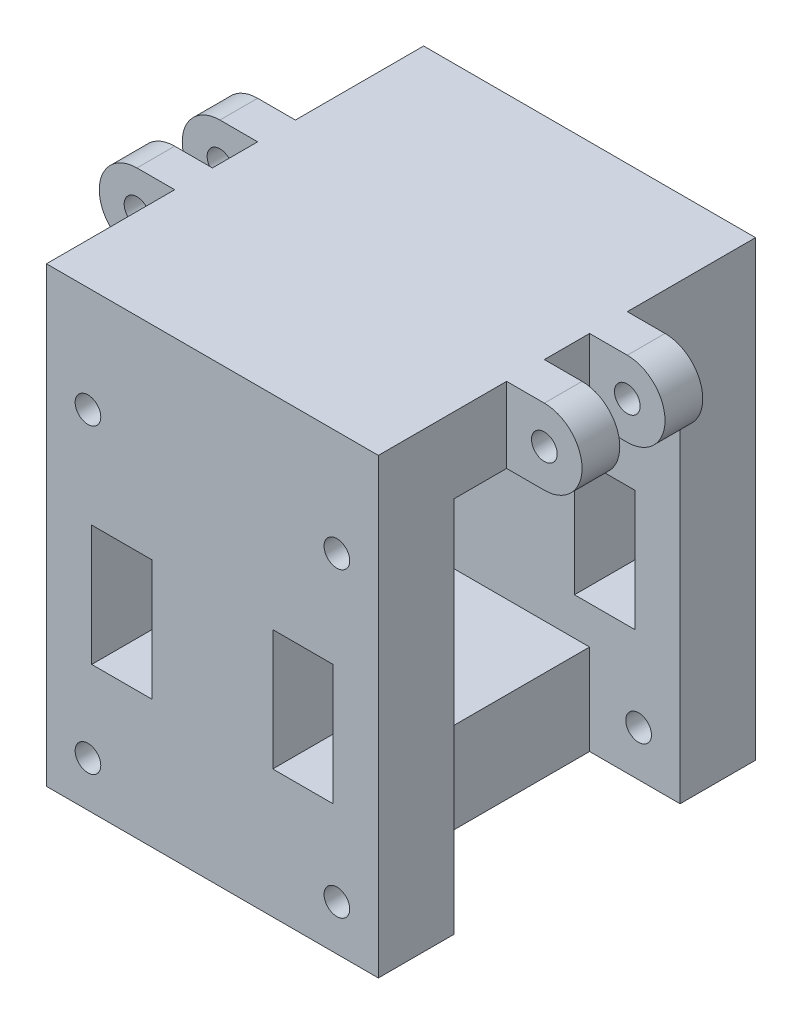
SolidWorks part; units mm, degrees
ref_plane "Front Plane" through (0, 0, 0) normal (0, 0, 1) x (1, 0, 0)
ref_plane "Top Plane" through (0, 0, 0) normal (0, 1, 0) x (1, 0, 0)
ref_plane "Right Plane" through (0, 0, 0) normal (1, 0, 0) x (0, 0, -1)
sketch "Sketch1" plane through (0, 0, 0) normal (0, 0, 1) x (1, 0, 0)
  line L1 (-25, 30) -> (25, 30)
  line L2 (-25, 30) -> (-25, -30)
  line L3 (-25, -30) -> (25, -30)
  line L4 (25, 30) -> (25, -30)
  line L5 (-25, 30) -> (25, -30) construction
  line L6 (-25, -30) -> (25, 30) construction
  point P0 (0, 0)
  dimension "D1" = 50
  dimension "D2" = 60
extrude "Boss-Extrude1" add sketch "Sketch1" along normal blind 50
sketch "Sketch2" plane through (25, 0, 0) normal (1, 0, 0) x (0, 0, -1)
  line L0 (-50, -30) -> (0, -30) construction
  line L1 (-40, -30) -> (-10, -30)
  line L2 (-40, -30) -> (-40, 20)
  line L3 (-40, 20) -> (-10, 20)
  line L4 (-10, -30) -> (-10, 20)
  line L5 (-25, 30) -> (-25, -49970) construction
  line L6 (-50, 30) -> (0, 30) construction
  point P10 (-25, 30)
  point P11 (-25, -30)
  dimension "D1" = 30
  dimension "D2" = 10
extrude "Cut-Extrude1" cut sketch "Sketch2" against normal through all
sketch "Sketch3" plane through (0, 0, 50) normal (0, 0, 1) x (1, 0, 0)
  line L0 (-25, -30) -> (25, -30) construction
  line L1 (-25, 30) -> (-25, -30) construction
  line L2 (0, 0) -> (0, -50000) construction
  circle A0 centre (-16.5, -24) radius 1.7
  circle A1 centre (-16.5, 16) radius 1.7
  circle A2 centre (16.5, -24) radius 1.7
  circle A3 centre (16.5, 16) radius 1.7
  dimension "D1" = 3.4
  dimension "D2" = 6
  dimension "D3" = 8.5
  dimension "D4" = 3.4
  dimension "D5" = 40
  dimension "D6" = 8.5
extrude "Cut-Extrude2" cut sketch "Sketch3" against normal through all
sketch "Sketch4" plane through (0, 0, 50) normal (0, 0, 1) x (1, 0, 0)
  line L1 (0, 0) -> (0, -50000) construction
  line L10 (-25, 30) -> (-25, -30) construction
  line L11 (25, 30) -> (-25, 30) construction
  line L12 (-25, 30) -> (-25, 20)
  line L13 (-27, 20) -> (-25, 20)
  line L15 (-27, 30) -> (-25, 30)
  line L17 (27, 30) -> (25, 30)
  line L18 (27, 20) -> (25, 20)
  line L19 (25, 30) -> (25, 20)
  arc A4 (-27, 30) -> (-27, 20) centre (-27, 25) ccw
  circle A5 centre (-27, 25) radius 1.7
  circle A6 centre (27, 25) radius 1.7
  arc A7 (27, 30) -> (27, 20) centre (27, 25) cw
  dimension "D1" = 10
  dimension "D4" = 3.4
  dimension "D2" = 2
  dimension "D3" = 5
extrude "Boss-Extrude2" add sketch "Sketch4" against normal blind 50
sketch "Sketch6" plane through (0, 0, 50) normal (0, 0, 1) x (1, 0, 0)
  line L0 (0, 0) -> (0, -50000) construction
  line L8 (25, 30) -> (25, 20)
  line L9 (-27, 30) -> (-25, 30)
  line L11 (-27, 20) -> (-25, 20)
  line L12 (-25, 30) -> (-25, 20)
  line L13 (27, 20) -> (25, 20)
  line L14 (27, 30) -> (25, 30)
  arc A2 (-27, 30) -> (-27, 20) centre (-27, 25) ccw
  arc A3 (27, 30) -> (27, 20) centre (27, 25) cw
extrude "Cut-Extrude3" cut sketch "Sketch6" against normal blind 17
sketch "Sketch7" plane through (0, 30, 0) normal (0, 1, 0) x (1, 0, 0)
  line L0 (32, -28) -> (32, -22)
  line L5 (22, -22) -> (32, -22)
  line L6 (0, -50) -> (0, 49950) construction
  line L7 (25, -50) -> (-25, -50) construction
  line L12 (22, -28) -> (22, -22)
  line L13 (22, -28) -> (32, -28)
  line L16 (-32, 0) -> (-32, -33) construction
  line L17 (-22, -28) -> (-32, -28)
  line L18 (-22, -28) -> (-22, -22)
  line L19 (-22, -22) -> (-32, -22)
  line L20 (-32, -28) -> (-32, -22)
  line L21 (-25, -33) -> (-27, -33) construction
  point P12 (0, -50)
  dimension "D1" = 0
  dimension "D2" = 5
  dimension "D3" = 6
  dimension "D4" = 10
extrude "Cut-Extrude4" cut sketch "Sketch7" against normal blind 10
ref_plane "Plane1" through (0, 0, 25) normal (0, 0, -1) x (-1, 0, 0)
mirror "Mirror1" about plane through (0, 0, 25) normal (0, 0, -1) of "Cut-Extrude3"
sketch "Sketch8" plane through (0, 30, 0) normal (0, 1, 0) x (1, 0, 0)
  line L0 (25, -50) -> (-25, -50) construction
  line L1 (-25, -33) -> (-22, -33)
  line L2 (-25, -33) -> (-25, -50)
  line L3 (-25, -50) -> (-22, -50)
  line L4 (-22, -33) -> (-22, -50)
  line L5 (-22, -28) -> (-22, -22) construction
  line L6 (0, 0) -> (0, -50000) construction
  line L7 (22, -25) -> (-49978, -25) construction
  line L8 (22, -22) -> (22, -28) construction
  line L9 (-25, 0) -> (-22, 0)
  line L10 (-22, -17) -> (-22, 0)
  line L11 (-25, -17) -> (-22, -17)
  line L12 (-25, -17) -> (-25, 0)
  line L13 (25, -50) -> (22, -50)
  line L14 (22, -33) -> (22, -50)
  line L15 (25, -33) -> (22, -33)
  line L16 (25, -33) -> (25, -50)
  line L17 (25, -17) -> (25, 0)
  line L18 (25, -17) -> (22, -17)
  line L19 (22, -17) -> (22, 0)
  line L20 (25, 0) -> (22, 0)
  point P16 (22, -25)
  dimension "D1" = 0
extrude "Cut-Extrude5" cut sketch "Sketch8" against normal through all
sketch "Sketch10" plane through (0, 0, 10) normal (0, 0, 1) x (1, 0, 0)
  line L0 (-22, -30) -> (-22, 30) construction
  line L1 (-10, -18) -> (10, -18)
  line L3 (-10, -30) -> (10, -30)
  line L5 (-22, -30) -> (22, -30) construction
  line L9 (-10, -18) -> (-10, -30)
  line L11 (10, -18) -> (10, -30)
  dimension "D1" = 12
  dimension "D2" = 20
  dimension "D3" = 12
  dimension "D4" = 0
extrude "Boss-Extrude3" add sketch "Sketch10" along normal through all
sketch "Sketch12" plane through (0, 0, 50) normal (0, 0, 1) x (1, 0, 0)
  line L0 (-22, -30) -> (-22, 30) construction
  line L1 (-16, 3) -> (-8, 3)
  line L2 (-16, 3) -> (-16, -13)
  line L3 (-16, -13) -> (-8, -13)
  line L4 (-8, 3) -> (-8, -13)
  line L5 (22, 30) -> (-22, 30) construction
  line L6 (0, -30) -> (0, 49970) construction
  line L7 (-22, -30) -> (22, -30) construction
  line L8 (16, -13) -> (8, -13)
  line L9 (8, 3) -> (8, -13)
  line L10 (16, 3) -> (8, 3)
  line L11 (16, 3) -> (16, -13)
  point P12 (0, -30)
  dimension "D1" = 8
  dimension "D2" = 16
  dimension "D3" = 6
  dimension "D4" = 27
extrude "Cut-Extrude6" cut sketch "Sketch12" against normal through all
sketch "Sketch13" plane through (0, 0, 50) normal (0, 0, 1) x (1, 0, 0)
  line L0 (-16, 3) -> (-16, -13) construction
  line L1 (-16, -13) -> (-8, -13) construction
  line L2 (-8, -13) -> (-8, 3) construction
  line L3 (-8, 3) -> (-16, 3) construction
  line L4 (-22, -30) -> (22, -30)
  line L5 (22, -30) -> (22, 30)
  line L6 (22, 30) -> (-22, 30)
  line L7 (-22, 30) -> (-22, -30)
  line L8 (-22, -30) -> (22, -30)
  line L9 (22, -30) -> (22, 30)
  line L10 (22, 30) -> (-22, 30)
  line L11 (-22, 30) -> (-22, -30)
  line L12 (-16, 3) -> (-16, -13)
  line L13 (-16, -13) -> (-8, -13)
  line L14 (-8, -13) -> (-8, 3)
  line L15 (-8, 3) -> (-16, 3)
  line L16 (8, -13) -> (16, -13) construction
  line L17 (16, -13) -> (16, 3) construction
  line L18 (8, 3) -> (8, -13) construction
  line L19 (16, 3) -> (8, 3) construction
  line L20 (8, -13) -> (16, -13)
  line L21 (16, -13) -> (16, 3)
  line L22 (8, 3) -> (8, -13)
  line L23 (16, 3) -> (8, 3)
  dimension "D1" = 0
